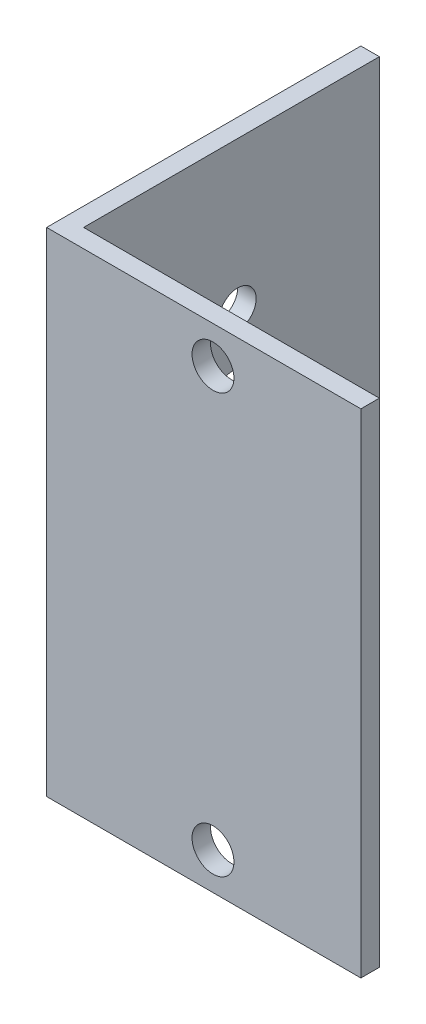
SolidWorks part; units mm, degrees
ref_plane "Front Plane" through (0, 0, 0) normal (0, 0, 1) x (1, 0, 0)
ref_plane "Top Plane" through (0, 0, 0) normal (0, 1, 0) x (1, 0, 0)
ref_plane "Right Plane" through (0, 0, 0) normal (1, 0, 0) x (0, 0, -1)
sketch "Sketch2" plane through (0, 0, 0) normal (0, 1, 0) x (1, 0, 0)
  line L0 (0, 0) -> (0, 24)
  line L1 (0, 24) -> (-1.5, 24)
  line L2 (-1.5, 24) -> (-1.5, -1.5)
  line L3 (-1.5, -1.5) -> (24, -1.5)
  line L4 (24, -1.5) -> (24, 0)
  line L5 (24, 0) -> (0, 0)
  dimension "D1" = 1.5
  dimension "D2" = 24
  dimension "D3" = 24
extrude "Boss-Extrude1" add sketch "Sketch2" along normal blind 40
sketch "Sketch3" plane through (-1.5, 0, 0) normal (-1, 0, 0) x (0, 0, 1)
  circle A0 centre (-12.5, 12) radius 1.5 construction
  circle A1 centre (-12.5, 20) radius 12.5
  circle A2 centre (-12.5, 20) radius 12.5 construction
  circle A3 centre (-12.5, 28) radius 1.5 construction
  circle A4 centre (-12.5, 20) radius 3.5 construction
  circle A5 centre (-12.5, 12) radius 1.5
  circle A6 centre (-12.5, 28) radius 1.5
  circle A7 centre (-12.5, 20) radius 3.5 construction
  circle A8 centre (-12.5, 20) radius 3.9
  dimension "D1" = 0
  dimension "D2" = 0.4
extrude "Cut-Extrude1" cut sketch "Sketch3" against normal up to surface (1.5 mm away) contours A8 | A6 | A5 up to face at (0, 20, -12)
sketch "Sketch4" plane through (0, 0, 0) normal (0, 0, -1) x (-1, 0, 0)
  line L0 (-24, 3) -> (0, 3) construction
  line L1 (-24, 40) -> (-24, 0) construction
  line L2 (0, 40) -> (0, 0) construction
  line L3 (-24, 20) -> (0, 20) construction
  line L4 (-24, 0) -> (0, 0) construction
  circle A0 centre (-12, 3) radius 1.7
  circle A1 centre (-12, 37) radius 1.7
  dimension "D1" = 3.4
  dimension "D2" = 3
extrude "Cut-Extrude2" cut sketch "Sketch4" against normal blind 10
